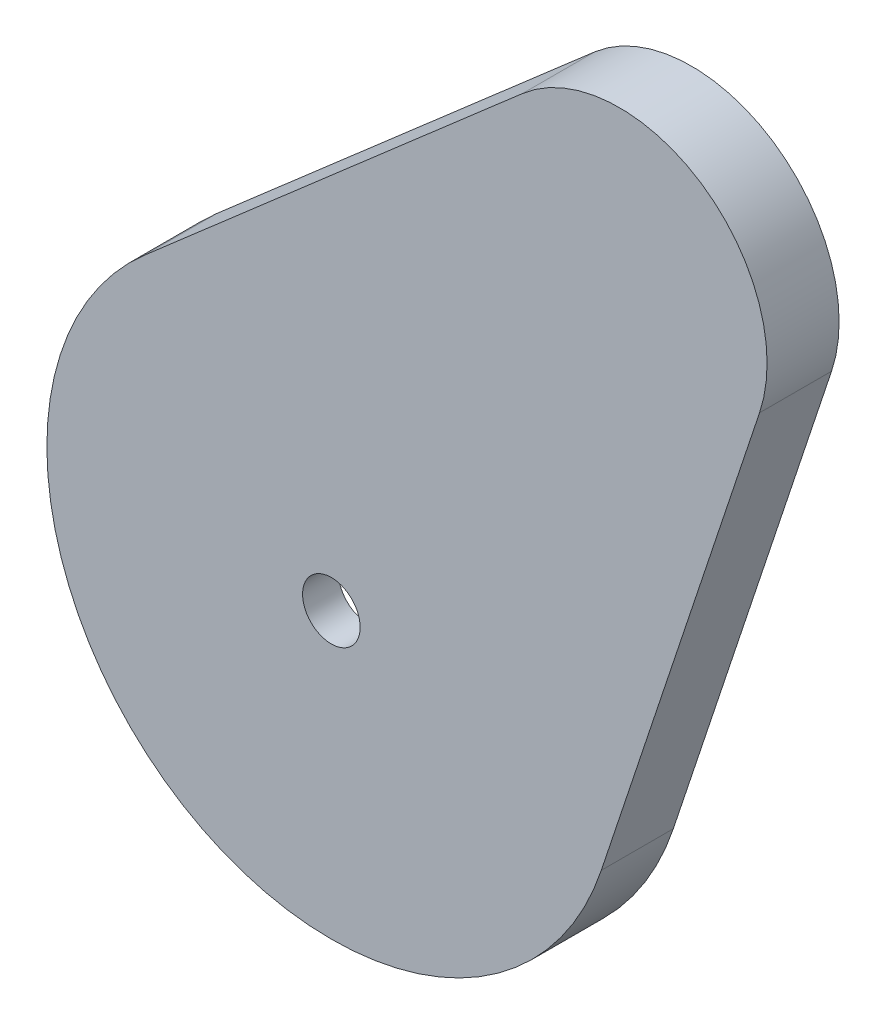
SolidWorks part; units mm, degrees
ref_plane "Plan de face" through (0, 0, 0) normal (0, 0, 1) x (1, 0, 0)
ref_plane "Plan de dessus" through (0, 0, 0) normal (0, 1, 0) x (1, 0, 0)
ref_plane "Plan de droite" through (0, 0, 0) normal (1, 0, 0) x (0, 0, -1)
sketch "Esquisse1" plane through (0, 0, 0) normal (0, 0, 1) x (1, 0, 0)
  line L0 (16.5878, 53.8432) -> (-35.8856, 8.1755)
  line L1 (27.5237, -34.0974) -> (49.4965, 31.9041)
  line L2 (23.1528, 46.2999) -> (-29.3206, 0.6322)
  line L3 (18.0357, -30.9387) -> (40.0084, 35.0628)
  arc A0 (-35.8856, 8.1755) -> (27.5237, -34.0974) centre (-9.954, -21.6206) ccw
  arc A1 (49.4965, 31.9041) -> (16.5878, 53.8432) centre (30.046, 38.3794) ccw
  arc A2 (40.0084, 35.0628) -> (23.1528, 46.2999) centre (30.046, 38.3794) ccw
  arc A3 (-29.3206, 0.6322) -> (18.0357, -30.9387) centre (-9.954, -21.6206) ccw
extrude "Boss.-Extru.1" add sketch "Esquisse1" along normal blind 5
sketch "Esquisse2" plane through (0, 0, 5) normal (0, 0, 1) x (1, 0, 0)
  line L2 (16.5878, 53.8432) -> (-35.8856, 8.1755)
  line L3 (27.5237, -34.0974) -> (49.4965, 31.9041)
  line L4 (16.5878, 53.8432) -> (-35.8856, 8.1755)
  line L5 (27.5237, -34.0974) -> (49.4965, 31.9041)
  arc A2 (49.4965, 31.9041) -> (16.5878, 53.8432) centre (30.046, 38.3794) ccw
  arc A3 (-35.8856, 8.1755) -> (27.5237, -34.0974) centre (-9.954, -21.6206) ccw
  arc A4 (49.4965, 31.9041) -> (16.5878, 53.8432) centre (30.046, 38.3794) ccw
  arc A5 (-35.8856, 8.1755) -> (27.5237, -34.0974) centre (-9.954, -21.6206) ccw
  dimension "D1" = 0
extrude "Boss.-Extru.2" add sketch "Esquisse2" along normal blind 5
sketch "Esquisse3" plane through (0, 0, 10) normal (0, 0, 1) x (1, 0, 0)
  circle A0 centre (-9.954, -21.6206) radius 4
  dimension "D1" = 8
extrude "Enlèv. mat.-Extru.1" cut sketch "Esquisse3" against normal blind 5
